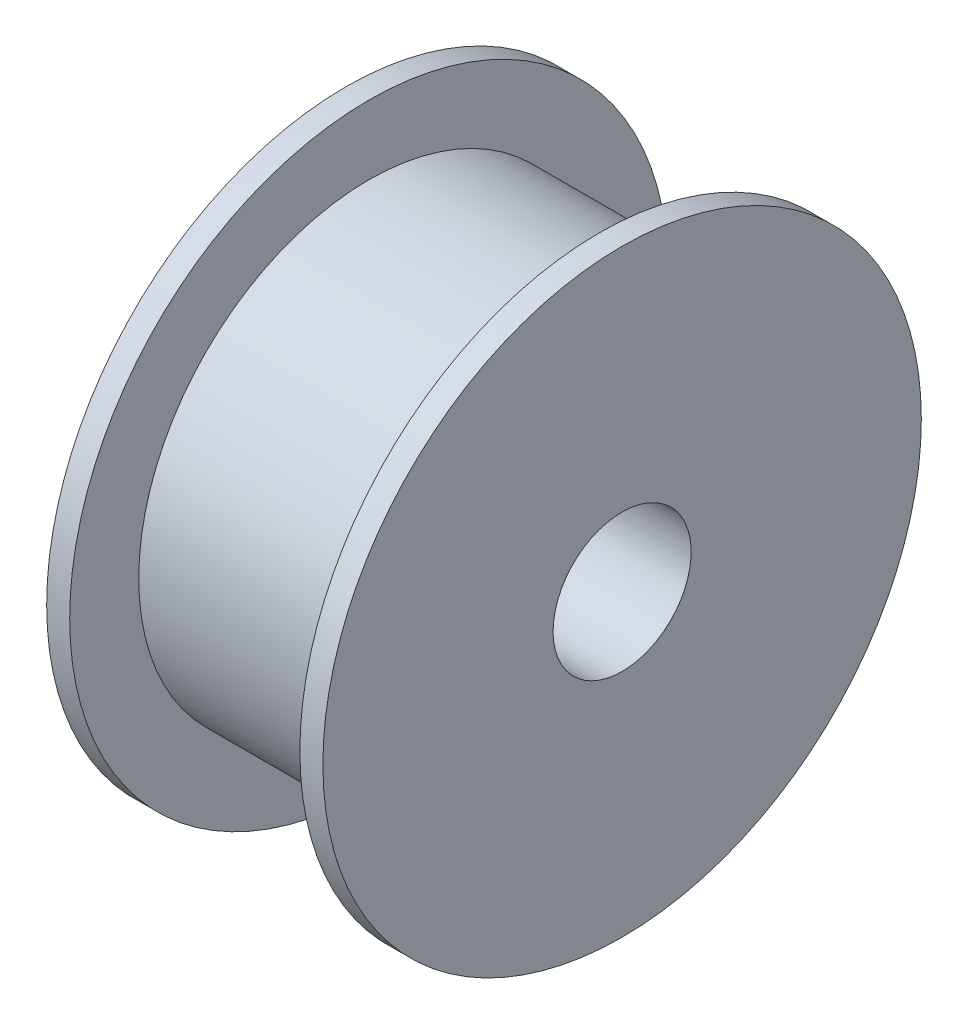
SolidWorks part; units mm, degrees
ref_plane "Front Plane" through (0, 0, 0) normal (0, 0, 1) x (1, 0, 0)
ref_plane "Top Plane" through (0, 0, 0) normal (0, 1, 0) x (1, 0, 0)
ref_plane "Right Plane" through (0, 0, 0) normal (1, 0, 0) x (0, 0, -1)
sketch "Sketch1" plane through (0, 0, 0) normal (0, 0, 1) x (1, 0, 0)
  line L0 (-6, 3) -> (-5, 3)
  line L1 (-5, 3) -> (-5, 0)
  line L2 (-5, 0) -> (5, 0)
  line L3 (-6, 3) -> (-6, -10)
  line L4 (-6, -10) -> (6, -10)
  line L6 (6, 3) -> (5, 3)
  line L7 (5, 3) -> (5, 0)
  line L8 (6, 3) -> (6, -10)
  point P3 (0, 0)
  dimension "D1" = 13
  dimension "D2" = 3
  dimension "D3" = 1
revolve "Revolve1" add sketch "Sketch1" angle 360 about L4
sketch "Sketch2" plane through (-6, 0, 0) normal (-1, 0, 0) x (0, 0, 1)
  circle A0 centre (0, -10) radius 3
  dimension "D1" = 6
extrude "Cut-Extrude1" cut sketch "Sketch2" against normal through all
